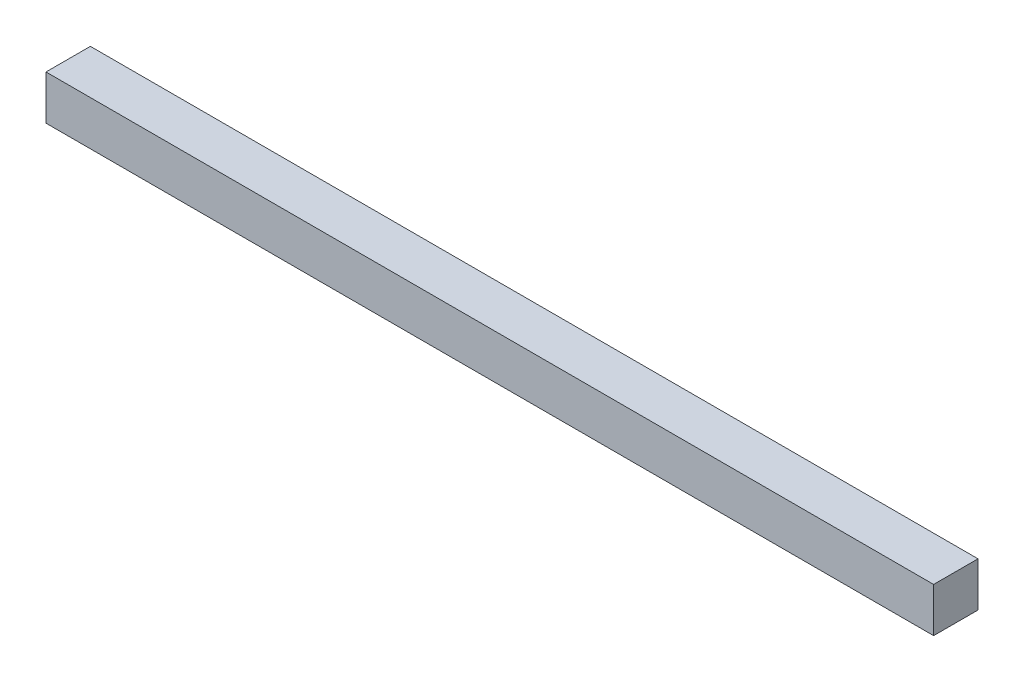
SolidWorks part; units mm, degrees
ref_plane "Front Plane" through (0, 0, 0) normal (0, 0, 1) x (1, 0, 0)
ref_plane "Top Plane" through (0, 0, 0) normal (0, 1, 0) x (1, 0, 0)
ref_plane "Right Plane" through (0, 0, 0) normal (1, 0, 0) x (0, 0, -1)
sketch "Sketch1" plane through (0, 0, 0) normal (1, 0, 0) x (0, 0, -1)
  line L1 (-10, -10) -> (10, -10)
  line L2 (-10, -10) -> (-10, 10)
  line L3 (-10, 10) -> (10, 10)
  line L4 (10, -10) -> (10, 10)
  line L5 (-10, -10) -> (10, 10) construction
  line L6 (-10, 10) -> (10, -10) construction
  point P0 (0, 0)
  dimension "D1" = 20
  dimension "D2" = 20
extrude "Boss-Extrude1" add sketch "Sketch1" along normal blind 400
